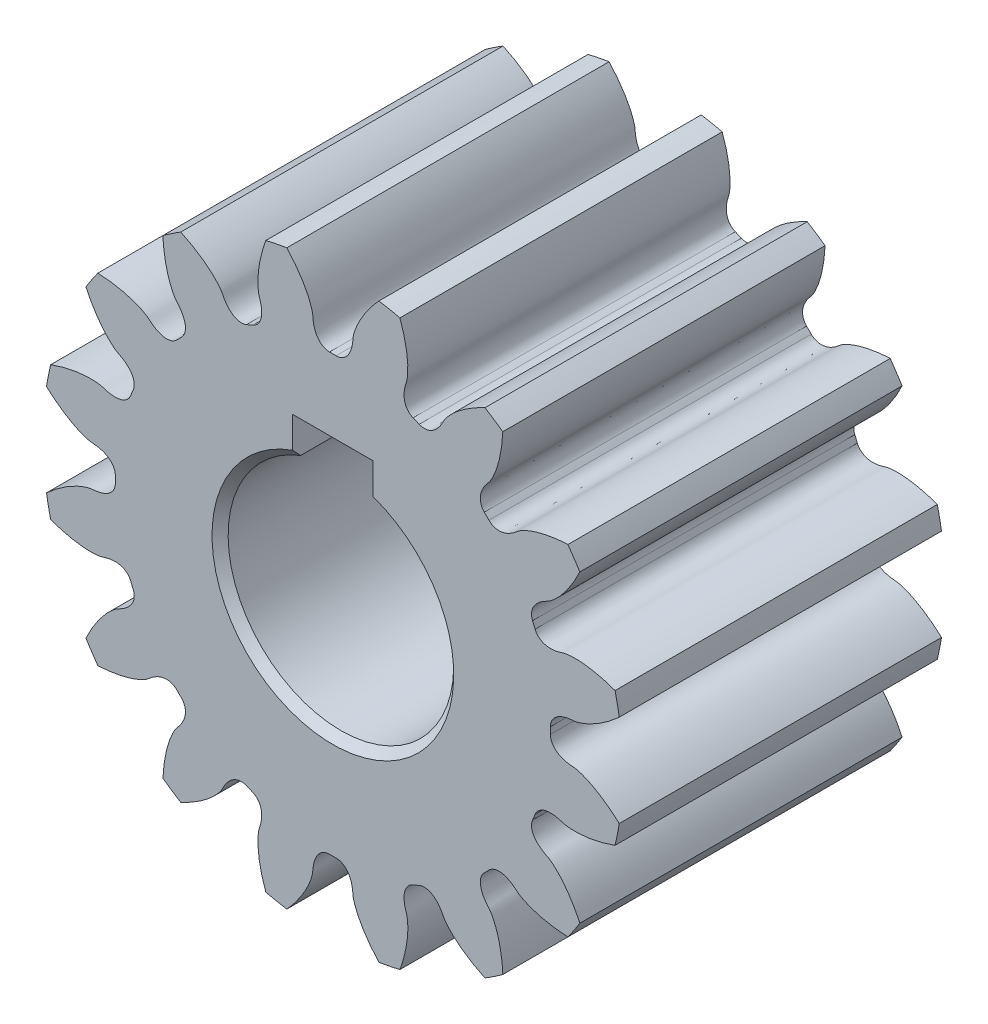
SolidWorks part; units mm, degrees
ref_plane "前视基准面" through (0, 0, 0) normal (0, 0, 1) x (1, 0, 0)
ref_plane "上视基准面" through (0, 0, 0) normal (0, 1, 0) x (1, 0, 0)
ref_plane "右视基准面" through (0, 0, 0) normal (1, 0, 0) x (0, 0, -1)
ref_axis "基准轴1" through (0, 0, -88.99) along (0, 0, 1)
sketch "Gear-BaseSketch" plane through (0, 0, 0) normal (0, 0, 1) x (1, 0, 0)
  circle A0 centre (0, 0) radius 18
  dimension "D1" = 36
extrude "2.0 模数    , 32.0000mm P.D." add sketch "Gear-BaseSketch" along normal mid plane 20
sketch "Tooth-Sketch; Backlash: 0.0000mm" plane through (0, 0, 0) normal (0, 0, 1) x (1, 0, 0)
  line L0 (0, 0) -> (0, 22.5526) construction
  arc A0 (-2.9278, 17.8489) -> (2.9278, 17.8489) centre (0, 0) cw
  arc A1 (-0.2031, 13.4985) -> (0.2031, 13.4985) centre (0, 0) cw
  spline S0 degree 3 poles (-2.9278, 17.8489) (-2.8304, 17.7422) (-2.6424, 17.5362) (-2.3874, 17.2232) (-2.1637, 16.924) (-1.9704, 16.6396) (-1.8057, 16.3724) (-1.6676, 16.1243) (-1.554, 15.897) (-1.4627, 15.6922) (-1.3916, 15.5114) (-1.3383, 15.3559) (-1.3002, 15.2269) (-1.2753, 15.1253) (-1.2481, 14.996) (-1.2453, 14.8619) (-1.2286, 14.7191) (-1.2131, 14.6143) (-1.1875, 14.4813) (-1.1462, 14.3228) (-1.0795, 14.1428) (-0.9928, 13.9741) (-0.8801, 13.8161) (-0.7315, 13.6721) (-0.5372, 13.5549) (-0.3506, 13.5052) (-0.2356, 13.5) (-0.2031, 13.4985) knots 0 0 0 0 0.08065 0.155737 0.225263 0.289226 0.347627 0.400467 0.447744 0.489459 0.525613 0.556204 0.581233 0.6007 0.614605 0.654902 0.675198 0.694889 0.714022 0.750829 0.786204 0.820996 0.856424 0.894112 0.935742 0.981856 1 1 1 1
  spline S1 degree 3 poles (2.9278, 17.8489) (2.8304, 17.7422) (2.6424, 17.5362) (2.3874, 17.2232) (2.1637, 16.924) (1.9704, 16.6396) (1.8057, 16.3724) (1.6676, 16.1243) (1.554, 15.897) (1.4627, 15.6922) (1.3916, 15.5114) (1.3383, 15.3559) (1.3002, 15.2269) (1.2753, 15.1253) (1.2481, 14.996) (1.2453, 14.8619) (1.2286, 14.7191) (1.2131, 14.6143) (1.1875, 14.4813) (1.1462, 14.3228) (1.0795, 14.1428) (0.9928, 13.9741) (0.8801, 13.8161) (0.7315, 13.6721) (0.5372, 13.5549) (0.3506, 13.5052) (0.2356, 13.5) (0.2031, 13.4985) knots 0 0 0 0 0.08065 0.155737 0.225263 0.289226 0.347627 0.400467 0.447744 0.489459 0.525613 0.556204 0.581233 0.6007 0.614605 0.654902 0.675198 0.694889 0.714022 0.750829 0.786204 0.820996 0.856424 0.894112 0.935742 0.981856 1 1 1 1
extrude "Tooth-Cut, Coarse Pitch Involute 20 deg" cut sketch "Tooth-Sketch; Backlash: 0.0000mm" against normal through all and the other way through all
pattern_circular "阵列(圆周)1" count 16 over 360 about axis through (0, 0, -88.99) along (0, 0, 1) of "Tooth-Cut, Coarse Pitch Involute 20 deg"
sketch "草图3" plane through (0, 0, 10) normal (0, 0, 1) x (1, 0, 0)
  circle A0 centre (0, 0) radius 7
  dimension "D1" = 14
extrude "切除-拉伸2" cut sketch "草图3" against normal blind 100
sketch "草图4" plane through (0, 0, -10) normal (0, 0, -1) x (-1, 0, 0)
  line L1 (-2.5, 9) -> (2.5, 9)
  line L2 (-2.5, 9) -> (-2.5, 2.2059)
  line L3 (-2.5, 2.2059) -> (2.5, 2.2059)
  line L4 (2.5, 9) -> (2.5, 2.2059)
extrude "切除-拉伸3" cut sketch "草图4" against normal through all
chamfer "倒角1" distance 0.5 angle 45 2 edges at (0, -7, 10) (0, -7, -10)
